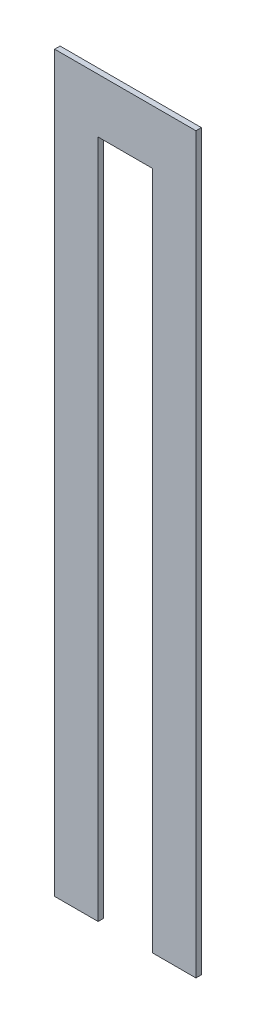
SolidWorks part; units mm, degrees
ref_plane "前视基准面" through (0, 0, 0) normal (0, 0, 1) x (1, 0, 0)
ref_plane "上视基准面" through (0, 0, 0) normal (0, 1, 0) x (1, 0, 0)
ref_plane "右视基准面" through (0, 0, 0) normal (1, 0, 0) x (0, 0, -1)
sketch "草图1" plane through (0, 0, 0) normal (0, 0, 1) x (1, 0, 0)
  line L0 (-2.5, 0) -> (-2.5, 62.5)
  line L1 (-6.5, 67.5) -> (6.5, 67.5)
  line L2 (-6.5, 67.5) -> (-6.5, 0)
  line L3 (-6.5, 0) -> (-2.5, 0)
  line L4 (6.5, 67.5) -> (6.5, 0)
  line L5 (-2.5, 62.5) -> (2.5, 62.5)
  line L6 (2.5, 62.5) -> (2.5, 0)
  line L7 (2.5, 0) -> (6.5, 0)
  dimension "D1" = 67.5
  dimension "D2" = 13
  dimension "D3" = 6.5
  dimension "D4" = 5
  dimension "D5" = 2.5
  dimension "D6" = 5
extrude "凸台-拉伸1" add sketch "草图1" along normal blind 0.5
